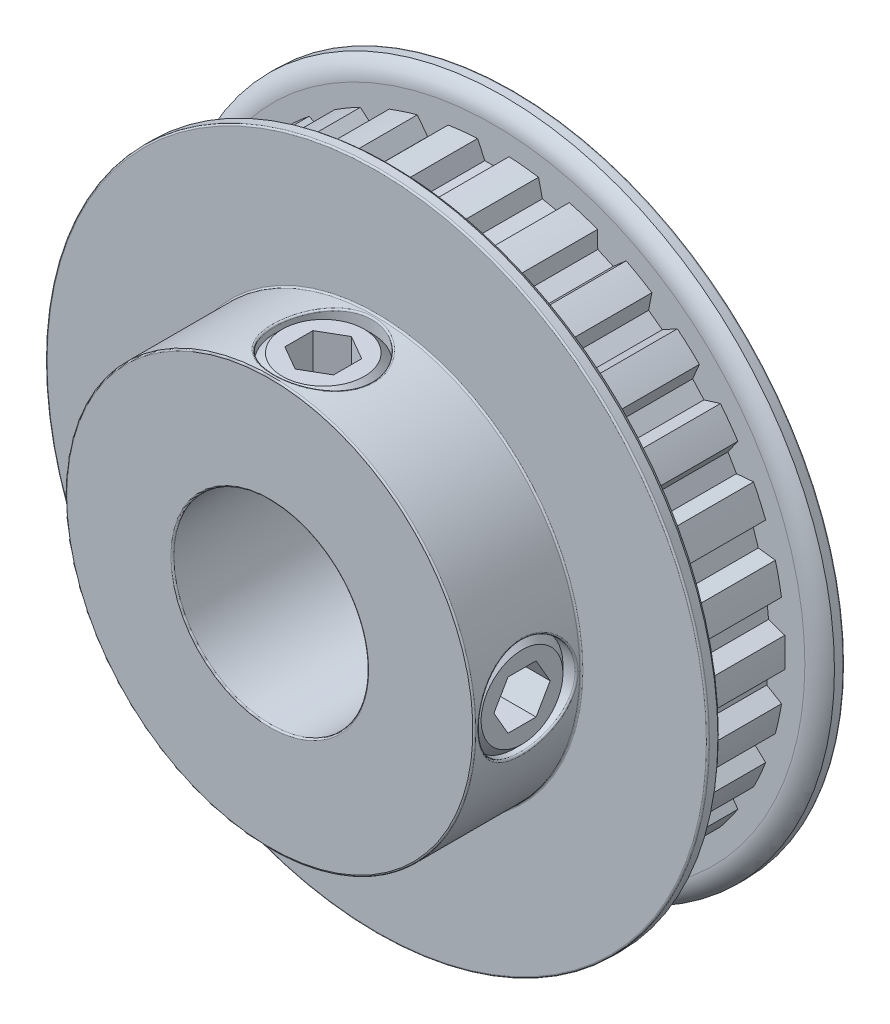
SolidWorks part; units mm, degrees
ref_plane "Front Plane" through (0, 0, 0) normal (0, 0, 1) x (1, 0, 0)
ref_plane "Top Plane" through (0, 0, 0) normal (0, 1, 0) x (1, 0, 0)
ref_plane "Right Plane" through (0, 0, 0) normal (1, 0, 0) x (0, 0, -1)
sketch "Sketch1" plane through (0, 0, 0) normal (0, 0, 1) x (1, 0, 0)
  line L0 (-1.2827, 23.749) -> (-0.6905, 22.479)
  line L1 (-0.6905, 22.479) -> (0.6905, 22.479)
  line L2 (0.6905, 22.479) -> (1.2827, 23.749)
  line L3 (-1.2827, 23.749) -> (1.2827, 23.749)
  line L4 (0, 0) -> (0, 22.479) construction
  line L5 (0, 22.479) -> (0, 24.765) construction
  circle A0 centre (0, 0) radius 24.257 construction
  circle A1 centre (0, 0) radius 26.9875 construction
  circle A2 centre (0, 0) radius 23.7836 construction
  point P6 (0, 23.749)
  point P11 (0, 24.257)
  point P13 (0, 26.9875)
  point P14 (0, 23.7836)
  dimension "D1" = 1.016
  dimension "D2" = 0.508
sketch "Sketch2" plane through (0, 0, 0) normal (1, 0, 0) x (0, 0, -1)
  line L0 (-9.9187, 7.9375) -> (9.9187, 7.9375)
  line L1 (-9.9187, 7.9375) -> (-9.9187, 16.6751)
  line L2 (-9.9187, 16.6751) -> (-1.2065, 16.6751)
  line L3 (-1.2065, 16.6751) -> (-1.2065, 26.9875)
  line L4 (-1.2065, 26.9875) -> (0.4191, 26.9875) construction
  line L5 (0.4191, 26.9875) -> (0.4191, 23.7836) construction
  line L6 (0.4191, 23.7836) -> (8.2931, 23.7836)
  line L7 (8.2931, 23.7836) -> (8.2931, 26.9875) construction
  line L8 (8.2931, 26.9875) -> (9.9187, 26.9875) construction
  line L9 (9.9187, 26.9875) -> (9.9187, 7.9375)
  line L10 (-9.9187, 0) -> (9.9187, 0) construction
  line L13 (-1.2065, 26.9875) -> (-0.3937, 26.9875)
  line L14 (0.4191, 25.3856) -> (0.4191, 23.7836)
  line L15 (8.2931, 23.7836) -> (8.2931, 25.3856)
  line L16 (9.1059, 26.9875) -> (9.9187, 26.9875)
  arc A0 (0.4191, 25.3856) -> (-0.3937, 26.9875) centre (-1.5659, 25.3856) ccw
  arc A1 (8.2931, 25.3856) -> (9.1059, 26.9875) centre (10.2781, 25.3856) cw
  point P12 (0.4191, 25.3856)
  point P14 (-0.3937, 26.9875)
  point P20 (8.2931, 25.3856)
  point P21 (9.1059, 26.9875)
  point P25 (8.2931, 0)
  point P26 (0.4191, 0)
  dimension "Bore" = 15.875
  dimension "Hub Dia" = 33.3502
  dimension "Outside Width" = 11.1252
  dimension "Inside Width" = 7.874
revolve "Revolve1" add sketch "Sketch2" angle 360 mid plane about L10
sketch "Sketch3" plane through (0, 0, 0) normal (0, 0, 1) x (1, 0, 0)
  line L0 (-0.6905, 22.479) -> (0.6905, 22.479) construction
  line L1 (0.6905, 22.479) -> (1.2827, 23.749) construction
  line L2 (-1.2827, 23.749) -> (-0.6905, 22.479) construction
  line L3 (-0.6905, 22.479) -> (0.6905, 22.479)
  line L4 (0.6905, 22.479) -> (1.2827, 23.749)
  line L5 (-1.2827, 23.749) -> (-0.6905, 22.479)
  circle A0 centre (0, 0) radius 23.7836 construction
  arc A1 (1.2827, 23.749) -> (-1.2827, 23.749) centre (0, 0) ccw
extrude "Cut-Extrude1" cut sketch "Sketch3" against normal up to vertex (8.2931 mm away) from vertex at -0.4191 starting at point (0, 23.7836, -0.4191)
pattern_circular "CirPattern1" count 30 over 360 about axis through (0, 0, 0) along (0, 0, 1) of "Cut-Extrude1"
sketch "Sketch4" plane through (0, 0, 0) normal (0, 1, 0) x (1, 0, 0)
  line L0 (0, -1.2065) -> (0, -9.9187) construction
  line L1 (-16.6751, -1.2065) -> (16.6751, -1.2065) construction
  line L2 (-16.6751, -9.9187) -> (16.6751, -9.9187) construction
  circle A0 centre (0, -5.5626) radius 3.9688
  dimension "D1" = 7.9375
extrude "Cut-Extrude2" cut sketch "Sketch4" along normal through all
ref_plane "Plane1" through (0, 0, 5.5626) normal (0, 0, 1) x (1, 0, 0)
sketch "Sketch5" plane through (0, 0, 5.5626) normal (0, 0, 1) x (1, 0, 0)
  line L0 (0, 0) -> (0, 16.6751) construction
  line L1 (-3.9688, 16.1959) -> (-3.9688, 6.8741) construction
  line L2 (-3.9688, 16.1959) -> (-3.9688, 6.8741) construction
  line L3 (0, 16.1959) -> (0, 7.9375)
  line L4 (0, 7.9375) -> (-3.3337, 7.9375)
  line L5 (-3.9688, 15.5609) -> (-3.9687, 8.5725)
  line L6 (-3.3337, 16.1959) -> (0, 16.1959)
  line L7 (-3.9688, 15.5609) -> (-3.3337, 16.1959)
  line L8 (-3.9687, 8.5725) -> (-3.3337, 7.9375)
  circle A0 centre (0, 0) radius 16.6751 construction
  circle A3 centre (0, 0) radius 7.9375 construction
  point P13 (-3.9688, 7.9375)
  point P15 (-3.9688, 16.1959)
revolve "Revolve2" add sketch "Sketch5" angle 360 mid plane about L0
sketch "Sketch6" plane through (0, 16.1959, 0) normal (0, -1, 0) x (-1, 0, 0)
  line L1 (0, -3.2712) -> (-1.9844, -4.4169)
  line L2 (-1.9844, -4.4169) -> (-1.9844, -6.7083)
  line L3 (-1.9844, -6.7083) -> (0, -7.854)
  line L4 (0, -7.854) -> (1.9844, -6.7083)
  line L5 (1.9844, -6.7083) -> (1.9844, -4.4169)
  line L6 (1.9844, -4.4169) -> (0, -3.2712)
  circle A0 centre (0, -5.5626) radius 1.9844 construction
  dimension "D1" = 3.9688
extrude "Cut-Extrude3" cut sketch "Sketch6" along normal blind 2.9766
pattern_circular "CirPattern2" count 2 every 90 about axis through (0, 0, 0) along (0, 0, 1) of "Cut-Extrude2", "Revolve2", "Cut-Extrude3"
fillet "Fillet1" radius 0.127 8 edges at (7.9375, 0, -9.9187) (26.9875, 0, -9.9187) (16.6564, -0.7887, 9.4522) (0.7887, 16.6564, 9.4522) (26.9875, 0, 1.2065) (16.6751, 0, 1.2065) (16.6751, 0, 9.9187) (7.9375, 0, 9.9187)
equation "\"D2@Sketch1\" = \"D1@Sketch1\"/2"
equation "\"D1@Sketch4\" = \"Bore@Sketch2\"/2"
equation "\"D1@Sketch6\" = \"D1@Sketch4\"/2"
equation "\"D1@Cut-Extrude3\" = \"D1@Sketch6\"*.75"
